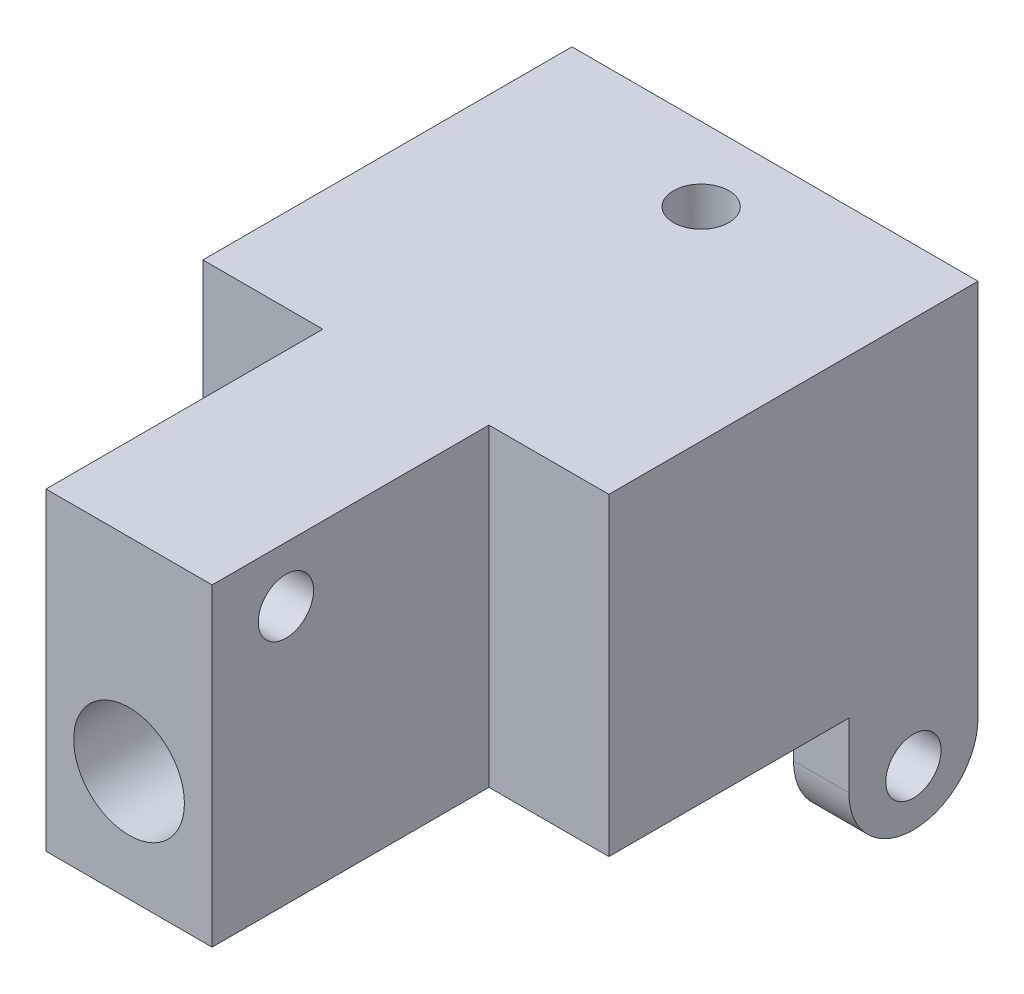
SolidWorks part; units mm, degrees
ref_plane "Płaszczyzna przednia" through (0, 0, 0) normal (0, 0, 1) x (1, 0, 0)
ref_plane "Płaszczyzna górna" through (0, 0, 0) normal (0, 1, 0) x (1, 0, 0)
ref_plane "Płaszczyzna prawa" through (0, 0, 0) normal (1, 0, 0) x (0, 0, -1)
sketch "Szkic1" plane through (0, 0, 0) normal (0, 0, 1) x (1, 0, 0)
  line L1 (8, 6) -> (-8, 6)
  line L3 (8, -6) -> (-8, -6)
  line L5 (8, 6) -> (-8, -6) construction
  line L6 (8, -6) -> (-8, 6) construction
  line L7 (8, 6) -> (11, 6)
  line L8 (8, -6) -> (8, -13)
  line L9 (8, -13) -> (11, -13)
  line L10 (11, 6) -> (11, -13)
  line L11 (-8, 6) -> (-11, 6)
  line L12 (-8, -6) -> (-8, -13)
  line L13 (-8, -13) -> (-11, -13)
  line L14 (-11, 6) -> (-11, -13)
  point P0 (0, 0)
  dimension "D1" = 16
  dimension "D2" = 12
  dimension "D3" = 7
  dimension "D4" = 7
  dimension "D5" = 3
  dimension "D6" = 3
extrude "Dodanie-wyciągnięcie1" add sketch "Szkic1" along normal blind 7
sketch "Szkic2" plane through (-11, 0, 0) normal (-1, 0, 0) x (0, 0, 1)
  line L0 (7, -13) -> (0, -13) construction
  line L1 (0, -9.5) -> (0, -13)
  line L2 (0, -13) -> (7, -13)
  line L3 (7, -13) -> (7, -9.5)
  arc A0 (0, -9.5) -> (7, -9.5) centre (3.5, -9.5) ccw
  line M1 (0, 6) -> (0, -13)
  line M2 (0, -13) -> (7, -13)
  line M3 (7, -13) -> (7, 6)
  dimension "D1" = 7
  dimension "D2" = 3.5
extrude "Wytnij-wyciągnięcie1" cut sketch "Szkic2" against normal up to surface (22 mm away) contours A0 L2 M3 | A0 M1 M2 up to face at (11, -3.5, 3.5)
sketch "Szkic3" plane through (-11, 0, 0) normal (-1, 0, 0) x (0, 0, 1)
  line L0 (3.5, 6) -> (3.5, -13.7155) construction
  line L1 (7, 6) -> (0, 6) construction
  circle A0 centre (3.5, -10) radius 1.5
  arc A2 (0, -9.5) -> (7, -9.5) centre (3.5, -9.5) ccw construction
  dimension "D1" = 3
  dimension "D2" = 3
extrude "Wytnij-wyciągnięcie2" cut sketch "Szkic3" against normal up to surface (22 mm away) up to face at (11, -2.625, 3.5)
sketch "Szkic4" plane through (0, 0, 0) normal (0, 0, -1) x (-1, 0, 0)
  line L0 (8, -6) -> (11, -6) construction
  line L1 (11, 6) -> (11, -9.5) construction
  line L2 (-11, 6) -> (-11, 11.4053) construction
  line L3 (-11, 6) -> (11, 6) construction
  line L4 (11, -6) -> (-11, -6)
  line L5 (11, -6) -> (11, 11)
  line L6 (11, 11) -> (-11, 11)
  line L7 (-11, -6) -> (-11, 11)
  dimension "D1" = 5
extrude "Dodanie-wyciągnięcie2" add sketch "Szkic4" against normal blind 20 contours L6 L7 L4 L5
sketch "Szkic5" plane through (0, 0, 20) normal (0, 0, 1) x (1, 0, 0)
  circle A0 centre (0, 0) radius 3
  dimension "D1" = 6
extrude "Wytnij-wyciągnięcie3" cut sketch "Szkic5" against normal up to surface (20 mm away) up to face at (0, -3.5, 0)
ref_plane "Płaszczyzna4" through (0, 4, 0) normal (0, 1, 0) x (1, 0, 0)
sketch "Szkic6" plane through (0, 4, 0) normal (0, -1, 0) x (-1, 0, 0)
  line L0 (0, 0) -> (0, -0.7869) construction
  line L1 (2.65, -2.3168) -> (2.65, 0)
  line L2 (-2.65, -5.3768) -> (0, -6.9068)
  line L3 (0, -6.9068) -> (2.65, -5.3768)
  line L4 (2.65, -5.3768) -> (2.65, -2.3168)
  line L7 (-2.65, -2.3168) -> (-2.65, -5.3768)
  line L8 (3, 0) -> (-3, 0) construction
  line L9 (2.65, 0) -> (-2.65, 0)
  line L10 (-2.65, 0) -> (-2.65, -2.3168)
  line L11 (0, -1.1968) -> (0, -10.3286) construction
  line L12 (2.65, -2.3168) -> (1.325, -1.5519) [skipped]
  line L13 (-1.325, -1.5519) -> (-2.65, -2.3168) [skipped]
  circle A0 centre (0, -3.8468) radius 2.65 construction
  dimension "D1" = 5.3
extrude "Wytnij-wyciągnięcie4" cut sketch "Szkic6" against normal blind 2.5
sketch "Szkic7" plane through (0, 4, 0) normal (0, 1, 0) x (1, 0, 0)
  line L5 (-2.65, 0) -> (2.65, 0) construction
  circle A0 centre (0, -4) radius 1.5
  dimension "D1" = 3
  dimension "D2" = 4
extrude "Wytnij-wyciągnięcie5" cut sketch "Szkic7" against normal up to surface and the other way up to surface
sketch "Szkic8" plane through (0, 0, 20) normal (0, 0, 1) x (1, 0, 0)
  line L0 (-11, -6) -> (11, -6) construction
  line L1 (-4.5, -6) -> (4.5, -6)
  line L2 (-4.5, -6) -> (-4.5, 11)
  line L3 (-4.5, 11) -> (4.5, 11)
  line L4 (4.5, -6) -> (4.5, 11)
  line L5 (-11, 11) -> (11, 11) construction
  circle A0 centre (0, 0) radius 3
  circle A1 centre (0, 0) radius 3
  circle M3 centre (0, 0) radius 3
  line M5 (-11, -6) -> (11, -6)
  line M7 (11, 11) -> (-11, 11)
  dimension "D1" = 9
  dimension "D2" = 4.5
extrude "Dodanie-wyciągnięcie3" add sketch "Szkic8" along normal blind 15 contours L4 L2 M5 M7 M3
sketch "Szkic9" plane through (4.5, 0, 0) normal (1, 0, 0) x (0, 0, -1)
  line L0 (-35, 11) -> (-20, 11) construction
  line L2 (-35, -6) -> (-35, 11) construction
  circle A0 centre (-31, 8) radius 1.5
  point P6 (-35, 6.9976)
  dimension "D1" = 3
  dimension "D2" = 3
  dimension "D3" = 4
extrude "Wytnij-wyciągnięcie6" cut sketch "Szkic9" against normal up to surface (9 mm away) up to face at (-4.5, 2.5, 27.5)
